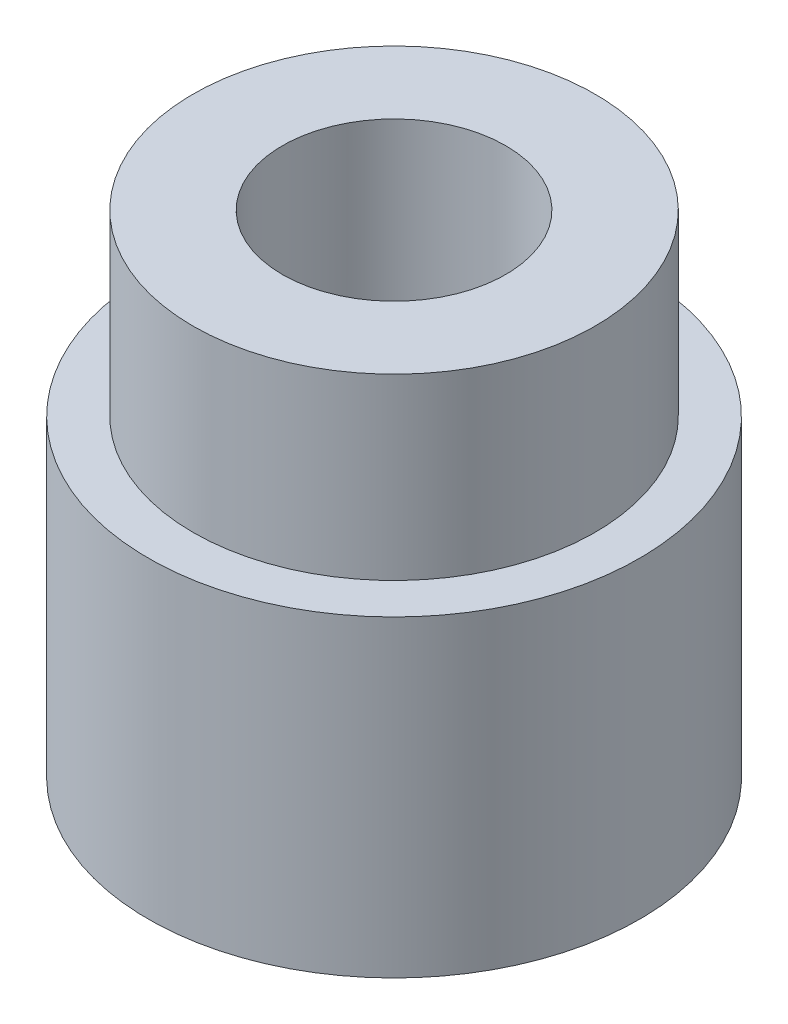
SolidWorks part; units mm, degrees
ref_plane "Front Plane" through (0, 0, 0) normal (0, 0, 1) x (1, 0, 0)
ref_plane "Top Plane" through (0, 0, 0) normal (0, 1, 0) x (1, 0, 0)
ref_plane "Right Plane" through (0, 0, 0) normal (1, 0, 0) x (0, 0, -1)
sketch "Sketch1" plane through (0, 0, 0) normal (0, 1, 0) x (1, 0, 0)
  circle A0 centre (0, 0) radius 4.5
  circle A1 centre (0, 0) radius 2.5
  dimension "D1" = 9
  dimension "D2" = 5
extrude "Boss-Extrude1" add sketch "Sketch1" along normal blind 4
sketch "Sketch2" plane through (0, 0, 0) normal (0, -1, 0) x (1, 0, 0)
  circle A0 centre (0, 0) radius 5.5
  circle A1 centre (0, 0) radius 2.5 construction
  circle A2 centre (0, 0) radius 2.5
  dimension "D1" = 11
extrude "Boss-Extrude2" add sketch "Sketch2" along normal blind 7
sketch "Sketch3" [suppressed] plane through (0, -7, 0) normal (0, -1, 0) x (1, 0, 0)
  line L0 (-0.1, 5.4991) -> (0, 5.3873)
  line L1 (0, 5.3873) -> (0.1, 5.4991)
  line L2 (0, 0) -> (0, 4.3381) construction
  line L3 (0.1033, 5.499) -> (0.1991, 5.3836)
  line L4 (0.1991, 5.3836) -> (0.3031, 5.4916)
  line L5 (0.3064, 5.4915) -> (0.3979, 5.3726)
  line L6 (0.3979, 5.3726) -> (0.5058, 5.4767)
  line L7 (0.5091, 5.4764) -> (0.5961, 5.3542)
  line L8 (0.5961, 5.3542) -> (0.7079, 5.4543)
  line L9 (0.7111, 5.4538) -> (0.7936, 5.3285)
  line L10 (0.7936, 5.3285) -> (0.9089, 5.4244)
  line L11 (0.9122, 5.4238) -> (0.9899, 5.2956)
  line L12 (0.9899, 5.2956) -> (1.1088, 5.3871)
  line L13 (1.112, 5.3864) -> (1.1849, 5.2554)
  line L14 (1.1849, 5.2554) -> (1.3071, 5.3424)
  line L15 (1.3102, 5.3417) -> (1.3783, 5.208)
  line L16 (1.3783, 5.208) -> (1.5036, 5.2905)
  line L17 (1.5067, 5.2896) -> (1.5698, 5.1535)
  line L18 (1.5698, 5.1535) -> (1.698, 5.2313)
  line L19 (1.7011, 5.2303) -> (1.7592, 5.092)
  line L20 (1.7592, 5.092) -> (1.8902, 5.165)
  line L21 (1.8933, 5.1639) -> (1.9461, 5.0235)
  line L22 (1.9461, 5.0235) -> (2.0797, 5.0916)
  line L23 (2.0828, 5.0904) -> (2.1304, 4.9482)
  line L24 (2.1304, 4.9482) -> (2.2665, 5.0113)
  line L25 (2.2694, 5.01) -> (2.3118, 4.8661)
  line L26 (2.3118, 4.8661) -> (2.4501, 4.9241)
  line L27 (2.453, 4.9227) -> (2.49, 4.7773)
  line L28 (2.49, 4.7773) -> (2.6304, 4.8302)
  line L29 (2.6332, 4.8287) -> (2.6649, 4.682)
  line L30 (2.6649, 4.682) -> (2.8071, 4.7297)
  line L31 (2.8099, 4.7281) -> (2.836, 4.5804)
  line L32 (2.836, 4.5804) -> (2.9799, 4.6228)
  line L33 (2.9827, 4.621) -> (3.0034, 4.4724)
  line L34 (3.0034, 4.4724) -> (3.1487, 4.5095)
  line L35 (3.1514, 4.5076) -> (3.1666, 4.3584)
  line L36 (3.1666, 4.3584) -> (3.3132, 4.3901)
  line L37 (3.3158, 4.3881) -> (3.3255, 4.2384)
  line L38 (3.3255, 4.2384) -> (3.4731, 4.2647)
  line L39 (3.4757, 4.2626) -> (3.4798, 4.1126)
  line L40 (3.4798, 4.1126) -> (3.6284, 4.1334)
  line L41 (3.6308, 4.1312) -> (3.6294, 3.9813)
  line L42 (3.6294, 3.9813) -> (3.7786, 3.9965)
  line L43 (3.781, 3.9943) -> (3.774, 3.8444)
  line L44 (3.774, 3.8444) -> (3.9237, 3.8542)
  line L45 (3.926, 3.8518) -> (3.9135, 3.7023)
  line L46 (3.9135, 3.7023) -> (4.0634, 3.7065)
  line L47 (4.0656, 3.7041) -> (4.0476, 3.5552)
  line L48 (4.0476, 3.5552) -> (4.1976, 3.5539)
  line L49 (4.1997, 3.5514) -> (4.1762, 3.4032)
  line L50 (4.1762, 3.4032) -> (4.3261, 3.3963)
  line L51 (4.3281, 3.3937) -> (4.2991, 3.2466)
  line L52 (4.2991, 3.2466) -> (4.4486, 3.2341)
  line L53 (4.4506, 3.2315) -> (4.4162, 3.0855)
  line L54 (4.4162, 3.0855) -> (4.5651, 3.0675)
  line L55 (4.5669, 3.0648) -> (4.5272, 2.9202)
  line L56 (4.5272, 2.9202) -> (4.6753, 2.8968)
  line L57 (4.6771, 2.894) -> (4.632, 2.7509)
  line L58 (4.632, 2.7509) -> (4.7792, 2.722)
  line L59 (4.7808, 2.7192) -> (4.7305, 2.5779)
  line L60 (4.7305, 2.5779) -> (4.8765, 2.5436)
  line L61 (4.878, 2.5407) -> (4.8225, 2.4013)
  line L62 (4.8225, 2.4013) -> (4.9672, 2.3616)
  line L63 (4.9686, 2.3587) -> (4.9079, 2.2215)
  line L64 (4.9079, 2.2215) -> (5.051, 2.1765)
  line L65 (5.0523, 2.1735) -> (4.9867, 2.0386)
  line L66 (4.9867, 2.0386) -> (5.128, 1.9884)
  line L67 (5.1292, 1.9853) -> (5.0586, 1.853)
  line L68 (5.0586, 1.853) -> (5.198, 1.7975)
  line L69 (5.199, 1.7944) -> (5.1236, 1.6648)
  line L70 (5.1236, 1.6648) -> (5.2608, 1.6042)
  line L71 (5.2618, 1.6011) -> (5.1816, 1.4743)
  line L72 (5.1816, 1.4743) -> (5.3165, 1.4087)
  line L73 (5.3174, 1.4056) -> (5.2326, 1.2818)
  line L74 (5.2326, 1.2818) -> (5.365, 1.2113)
  line L75 (5.3657, 1.2081) -> (5.2764, 1.0876)
  line L76 (5.2764, 1.0876) -> (5.4061, 1.0122)
  line L77 (5.4067, 1.009) -> (5.3129, 0.8919)
  line L78 (5.3129, 0.8919) -> (5.4398, 0.8118)
  line L79 (5.4402, 0.8085) -> (5.3423, 0.695)
  line L80 (5.3423, 0.695) -> (5.466, 0.6102)
  line L81 (5.4664, 0.607) -> (5.3643, 0.4971)
  line L82 (5.3643, 0.4971) -> (5.4849, 0.4078)
  line L83 (5.4851, 0.4046) -> (5.379, 0.2985)
  line L84 (5.379, 0.2985) -> (5.4962, 0.2049)
  line L85 (5.4963, 0.2016) -> (5.3864, 0.0996)
  line L86 (5.3864, 0.0996) -> (5.5, 0.0016)
  line L87 (5.5, -0.0016) -> (5.3864, -0.0996)
  line L88 (5.3864, -0.0996) -> (5.4963, -0.2016)
  line L89 (5.4962, -0.2049) -> (5.379, -0.2985)
  line L90 (5.379, -0.2985) -> (5.4851, -0.4046)
  line L91 (5.4849, -0.4078) -> (5.3643, -0.4971)
  line L92 (5.3643, -0.4971) -> (5.4664, -0.607)
  line L93 (5.466, -0.6102) -> (5.3423, -0.695)
  line L94 (5.3423, -0.695) -> (5.4402, -0.8085)
  line L95 (5.4398, -0.8118) -> (5.3129, -0.8919)
  line L96 (5.3129, -0.8919) -> (5.4067, -1.009)
  line L97 (5.4061, -1.0122) -> (5.2764, -1.0876)
  line L98 (5.2764, -1.0876) -> (5.3657, -1.2081)
  line L99 (5.365, -1.2113) -> (5.2326, -1.2818)
  line L100 (5.2326, -1.2818) -> (5.3174, -1.4056)
  line L101 (5.3165, -1.4087) -> (5.1816, -1.4743)
  line L102 (5.1816, -1.4743) -> (5.2618, -1.6011)
  line L103 (5.2608, -1.6042) -> (5.1236, -1.6648)
  line L104 (5.1236, -1.6648) -> (5.199, -1.7944)
  line L105 (5.198, -1.7975) -> (5.0586, -1.853)
  line L106 (5.0586, -1.853) -> (5.1292, -1.9853)
  line L107 (5.128, -1.9884) -> (4.9867, -2.0386)
  line L108 (4.9867, -2.0386) -> (5.0523, -2.1735)
  line L109 (5.051, -2.1765) -> (4.9079, -2.2215)
  line L110 (4.9079, -2.2215) -> (4.9686, -2.3587)
  line L111 (4.9672, -2.3616) -> (4.8225, -2.4013)
  line L112 (4.8225, -2.4013) -> (4.878, -2.5407)
  line L113 (4.8765, -2.5436) -> (4.7305, -2.5779)
  line L114 (4.7305, -2.5779) -> (4.7808, -2.7192)
  line L115 (4.7792, -2.722) -> (4.632, -2.7509)
  line L116 (4.632, -2.7509) -> (4.6771, -2.894)
  line L117 (4.6753, -2.8968) -> (4.5272, -2.9202)
  line L118 (4.5272, -2.9202) -> (4.5669, -3.0648)
  line L119 (4.5651, -3.0675) -> (4.4162, -3.0855)
  line L120 (4.4162, -3.0855) -> (4.4506, -3.2315)
  line L121 (4.4486, -3.2341) -> (4.2991, -3.2466)
  line L122 (4.2991, -3.2466) -> (4.3281, -3.3937)
  line L123 (4.3261, -3.3963) -> (4.1762, -3.4032)
  line L124 (4.1762, -3.4032) -> (4.1997, -3.5514)
  line L125 (4.1976, -3.5539) -> (4.0476, -3.5552)
  line L126 (4.0476, -3.5552) -> (4.0656, -3.7041)
  line L127 (4.0634, -3.7065) -> (3.9135, -3.7023)
  line L128 (3.9135, -3.7023) -> (3.926, -3.8518)
  line L129 (3.9237, -3.8542) -> (3.774, -3.8444)
  line L130 (3.774, -3.8444) -> (3.781, -3.9943)
  line L131 (3.7786, -3.9965) -> (3.6294, -3.9813)
  line L132 (3.6294, -3.9813) -> (3.6308, -4.1312)
  line L133 (3.6284, -4.1334) -> (3.4798, -4.1126)
  line L134 (3.4798, -4.1126) -> (3.4757, -4.2626)
  line L135 (3.4731, -4.2647) -> (3.3255, -4.2384)
  line L136 (3.3255, -4.2384) -> (3.3158, -4.3881)
  line L137 (3.3132, -4.3901) -> (3.1666, -4.3584)
  line L138 (3.1666, -4.3584) -> (3.1514, -4.5076)
  line L139 (3.1487, -4.5095) -> (3.0034, -4.4724)
  line L140 (3.0034, -4.4724) -> (2.9827, -4.621)
  line L141 (2.9799, -4.6228) -> (2.836, -4.5804)
  line L142 (2.836, -4.5804) -> (2.8099, -4.7281)
  line L143 (2.8071, -4.7297) -> (2.6649, -4.682)
  line L144 (2.6649, -4.682) -> (2.6332, -4.8287)
  line L145 (2.6304, -4.8302) -> (2.49, -4.7773)
  line L146 (2.49, -4.7773) -> (2.453, -4.9227)
  line L147 (2.4501, -4.9241) -> (2.3118, -4.8661)
  line L148 (2.3118, -4.8661) -> (2.2694, -5.01)
  line L149 (2.2665, -5.0113) -> (2.1304, -4.9482)
  line L150 (2.1304, -4.9482) -> (2.0828, -5.0904)
  line L151 (2.0797, -5.0916) -> (1.9461, -5.0235)
  line L152 (1.9461, -5.0235) -> (1.8933, -5.1639)
  line L153 (1.8902, -5.165) -> (1.7592, -5.092)
  line L154 (1.7592, -5.092) -> (1.7011, -5.2303)
  line L155 (1.698, -5.2313) -> (1.5698, -5.1535)
  line L156 (1.5698, -5.1535) -> (1.5067, -5.2896)
  line L157 (1.5036, -5.2905) -> (1.3783, -5.208)
  line L158 (1.3783, -5.208) -> (1.3102, -5.3417)
  line L159 (1.3071, -5.3424) -> (1.1849, -5.2554)
  line L160 (1.1849, -5.2554) -> (1.112, -5.3864)
  line L161 (1.1088, -5.3871) -> (0.9899, -5.2956)
  line L162 (0.9899, -5.2956) -> (0.9122, -5.4238)
  line L163 (0.9089, -5.4244) -> (0.7936, -5.3285)
  line L164 (0.7936, -5.3285) -> (0.7111, -5.4538)
  line L165 (0.7079, -5.4543) -> (0.5961, -5.3542)
  line L166 (0.5961, -5.3542) -> (0.5091, -5.4764)
  line L167 (0.5058, -5.4767) -> (0.3979, -5.3726)
  line L168 (0.3979, -5.3726) -> (0.3064, -5.4915)
  line L169 (0.3031, -5.4916) -> (0.1991, -5.3836)
  line L170 (0.1991, -5.3836) -> (0.1033, -5.499)
  line L171 (0.1, -5.4991) -> (0, -5.3873)
  line L172 (0, -5.3873) -> (-0.1, -5.4991)
  line L173 (-0.1033, -5.499) -> (-0.1991, -5.3836)
  line L174 (-0.1991, -5.3836) -> (-0.3031, -5.4916)
  line L175 (-0.3064, -5.4915) -> (-0.3979, -5.3726)
  line L176 (-0.3979, -5.3726) -> (-0.5058, -5.4767)
  line L177 (-0.5091, -5.4764) -> (-0.5961, -5.3542)
  line L178 (-0.5961, -5.3542) -> (-0.7079, -5.4543)
  line L179 (-0.7111, -5.4538) -> (-0.7936, -5.3285)
  line L180 (-0.7936, -5.3285) -> (-0.9089, -5.4244)
  line L181 (-0.9122, -5.4238) -> (-0.9899, -5.2956)
  line L182 (-0.9899, -5.2956) -> (-1.1088, -5.3871)
  line L183 (-1.112, -5.3864) -> (-1.1849, -5.2554)
  line L184 (-1.1849, -5.2554) -> (-1.3071, -5.3424)
  line L185 (-1.3102, -5.3417) -> (-1.3783, -5.208)
  line L186 (-1.3783, -5.208) -> (-1.5036, -5.2905)
  line L187 (-1.5067, -5.2896) -> (-1.5698, -5.1535)
  line L188 (-1.5698, -5.1535) -> (-1.698, -5.2313)
  line L189 (-1.7011, -5.2303) -> (-1.7592, -5.092)
  line L190 (-1.7592, -5.092) -> (-1.8902, -5.165)
  line L191 (-1.8933, -5.1639) -> (-1.9461, -5.0235)
  line L192 (-1.9461, -5.0235) -> (-2.0797, -5.0916)
  line L193 (-2.0828, -5.0904) -> (-2.1304, -4.9482)
  line L194 (-2.1304, -4.9482) -> (-2.2665, -5.0113)
  line L195 (-2.2694, -5.01) -> (-2.3118, -4.8661)
  line L196 (-2.3118, -4.8661) -> (-2.4501, -4.9241)
  line L197 (-2.453, -4.9227) -> (-2.49, -4.7773)
  line L198 (-2.49, -4.7773) -> (-2.6304, -4.8302)
  line L199 (-2.6332, -4.8287) -> (-2.6649, -4.682)
  line L200 (-2.6649, -4.682) -> (-2.8071, -4.7297)
  line L201 (-2.8099, -4.7281) -> (-2.836, -4.5804)
  line L202 (-2.836, -4.5804) -> (-2.9799, -4.6228)
  line L203 (-2.9827, -4.621) -> (-3.0034, -4.4724)
  line L204 (-3.0034, -4.4724) -> (-3.1487, -4.5095)
  line L205 (-3.1514, -4.5076) -> (-3.1666, -4.3584)
  line L206 (-3.1666, -4.3584) -> (-3.3132, -4.3901)
  line L207 (-3.3158, -4.3881) -> (-3.3255, -4.2384)
  line L208 (-3.3255, -4.2384) -> (-3.4731, -4.2647)
  line L209 (-3.4757, -4.2626) -> (-3.4798, -4.1126)
  line L210 (-3.4798, -4.1126) -> (-3.6284, -4.1334)
  line L211 (-3.6308, -4.1312) -> (-3.6294, -3.9813)
  line L212 (-3.6294, -3.9813) -> (-3.7786, -3.9965)
  line L213 (-3.781, -3.9943) -> (-3.774, -3.8444)
  line L214 (-3.774, -3.8444) -> (-3.9237, -3.8542)
  line L215 (-3.926, -3.8518) -> (-3.9135, -3.7023)
  line L216 (-3.9135, -3.7023) -> (-4.0634, -3.7065)
  line L217 (-4.0656, -3.7041) -> (-4.0476, -3.5552)
  line L218 (-4.0476, -3.5552) -> (-4.1976, -3.5539)
  line L219 (-4.1997, -3.5514) -> (-4.1762, -3.4032)
  line L220 (-4.1762, -3.4032) -> (-4.3261, -3.3963)
  line L221 (-4.3281, -3.3937) -> (-4.2991, -3.2466)
  line L222 (-4.2991, -3.2466) -> (-4.4486, -3.2341)
  line L223 (-4.4506, -3.2315) -> (-4.4162, -3.0855)
  line L224 (-4.4162, -3.0855) -> (-4.5651, -3.0675)
  line L225 (-4.5669, -3.0648) -> (-4.5272, -2.9202)
  line L226 (-4.5272, -2.9202) -> (-4.6753, -2.8968)
  line L227 (-4.6771, -2.894) -> (-4.632, -2.7509)
  line L228 (-4.632, -2.7509) -> (-4.7792, -2.722)
  line L229 (-4.7808, -2.7192) -> (-4.7305, -2.5779)
  line L230 (-4.7305, -2.5779) -> (-4.8765, -2.5436)
  line L231 (-4.878, -2.5407) -> (-4.8225, -2.4013)
  line L232 (-4.8225, -2.4013) -> (-4.9672, -2.3616)
  line L233 (-4.9686, -2.3587) -> (-4.9079, -2.2215)
  line L234 (-4.9079, -2.2215) -> (-5.051, -2.1765)
  line L235 (-5.0523, -2.1735) -> (-4.9867, -2.0386)
  line L236 (-4.9867, -2.0386) -> (-5.128, -1.9884)
  line L237 (-5.1292, -1.9853) -> (-5.0586, -1.853)
  line L238 (-5.0586, -1.853) -> (-5.198, -1.7975)
  line L239 (-5.199, -1.7944) -> (-5.1236, -1.6648)
  line L240 (-5.1236, -1.6648) -> (-5.2608, -1.6042)
  line L241 (-5.2618, -1.6011) -> (-5.1816, -1.4743)
  line L242 (-5.1816, -1.4743) -> (-5.3165, -1.4087)
  line L243 (-5.3174, -1.4056) -> (-5.2326, -1.2818)
  line L244 (-5.2326, -1.2818) -> (-5.365, -1.2113)
  line L245 (-5.3657, -1.2081) -> (-5.2764, -1.0876)
  line L246 (-5.2764, -1.0876) -> (-5.4061, -1.0122)
  line L247 (-5.4067, -1.009) -> (-5.3129, -0.8919)
  line L248 (-5.3129, -0.8919) -> (-5.4398, -0.8118)
  line L249 (-5.4402, -0.8085) -> (-5.3423, -0.695)
  line L250 (-5.3423, -0.695) -> (-5.466, -0.6102)
  line L251 (-5.4664, -0.607) -> (-5.3643, -0.4971)
  line L252 (-5.3643, -0.4971) -> (-5.4849, -0.4078)
  line L253 (-5.4851, -0.4046) -> (-5.379, -0.2985)
  line L254 (-5.379, -0.2985) -> (-5.4962, -0.2049)
  line L255 (-5.4963, -0.2016) -> (-5.3864, -0.0996)
  line L256 (-5.3864, -0.0996) -> (-5.5, -0.0016)
  line L257 (-5.5, 0.0016) -> (-5.3864, 0.0996)
  line L258 (-5.3864, 0.0996) -> (-5.4963, 0.2016)
  line L259 (-5.4962, 0.2049) -> (-5.379, 0.2985)
  line L260 (-5.379, 0.2985) -> (-5.4851, 0.4046)
  line L261 (-5.4849, 0.4078) -> (-5.3643, 0.4971)
  line L262 (-5.3643, 0.4971) -> (-5.4664, 0.607)
  line L263 (-5.466, 0.6102) -> (-5.3423, 0.695)
  line L264 (-5.3423, 0.695) -> (-5.4402, 0.8085)
  line L265 (-5.4398, 0.8118) -> (-5.3129, 0.8919)
  line L266 (-5.3129, 0.8919) -> (-5.4067, 1.009)
  line L267 (-5.4061, 1.0122) -> (-5.2764, 1.0876)
  line L268 (-5.2764, 1.0876) -> (-5.3657, 1.2081)
  line L269 (-5.365, 1.2113) -> (-5.2326, 1.2818)
  line L270 (-5.2326, 1.2818) -> (-5.3174, 1.4056)
  line L271 (-5.3165, 1.4087) -> (-5.1816, 1.4743)
  line L272 (-5.1816, 1.4743) -> (-5.2618, 1.6011)
  line L273 (-5.2608, 1.6042) -> (-5.1236, 1.6648)
  line L274 (-5.1236, 1.6648) -> (-5.199, 1.7944)
  line L275 (-5.198, 1.7975) -> (-5.0586, 1.853)
  line L276 (-5.0586, 1.853) -> (-5.1292, 1.9853)
  line L277 (-5.128, 1.9884) -> (-4.9867, 2.0386)
  line L278 (-4.9867, 2.0386) -> (-5.0523, 2.1735)
  line L279 (-5.051, 2.1765) -> (-4.9079, 2.2215)
  line L280 (-4.9079, 2.2215) -> (-4.9686, 2.3587)
  line L281 (-4.9672, 2.3616) -> (-4.8225, 2.4013)
  line L282 (-4.8225, 2.4013) -> (-4.878, 2.5407)
  line L283 (-4.8765, 2.5436) -> (-4.7305, 2.5779)
  line L284 (-4.7305, 2.5779) -> (-4.7808, 2.7192)
  line L285 (-4.7792, 2.722) -> (-4.632, 2.7509)
  line L286 (-4.632, 2.7509) -> (-4.6771, 2.894)
  line L287 (-4.6753, 2.8968) -> (-4.5272, 2.9202)
  line L288 (-4.5272, 2.9202) -> (-4.5669, 3.0648)
  line L289 (-4.5651, 3.0675) -> (-4.4162, 3.0855)
  line L290 (-4.4162, 3.0855) -> (-4.4506, 3.2315)
  line L291 (-4.4486, 3.2341) -> (-4.2991, 3.2466)
  line L292 (-4.2991, 3.2466) -> (-4.3281, 3.3937)
  line L293 (-4.3261, 3.3963) -> (-4.1762, 3.4032)
  line L294 (-4.1762, 3.4032) -> (-4.1997, 3.5514)
  line L295 (-4.1976, 3.5539) -> (-4.0476, 3.5552)
  line L296 (-4.0476, 3.5552) -> (-4.0656, 3.7041)
  line L297 (-4.0634, 3.7065) -> (-3.9135, 3.7023)
  line L298 (-3.9135, 3.7023) -> (-3.926, 3.8518)
  line L299 (-3.9237, 3.8542) -> (-3.774, 3.8444)
  line L300 (-3.774, 3.8444) -> (-3.781, 3.9943)
  line L301 (-3.7786, 3.9965) -> (-3.6294, 3.9813)
  line L302 (-3.6294, 3.9813) -> (-3.6308, 4.1312)
  line L303 (-3.6284, 4.1334) -> (-3.4798, 4.1126)
  line L304 (-3.4798, 4.1126) -> (-3.4757, 4.2626)
  line L305 (-3.4731, 4.2647) -> (-3.3255, 4.2384)
  line L306 (-3.3255, 4.2384) -> (-3.3158, 4.3881)
  line L307 (-3.3132, 4.3901) -> (-3.1666, 4.3584)
  line L308 (-3.1666, 4.3584) -> (-3.1514, 4.5076)
  line L309 (-3.1487, 4.5095) -> (-3.0034, 4.4724)
  line L310 (-3.0034, 4.4724) -> (-2.9827, 4.621)
  line L311 (-2.9799, 4.6228) -> (-2.836, 4.5804)
  line L312 (-2.836, 4.5804) -> (-2.8099, 4.7281)
  line L313 (-2.8071, 4.7297) -> (-2.6649, 4.682)
  line L314 (-2.6649, 4.682) -> (-2.6332, 4.8287)
  line L315 (-2.6304, 4.8302) -> (-2.49, 4.7773)
  line L316 (-2.49, 4.7773) -> (-2.453, 4.9227)
  line L317 (-2.4501, 4.9241) -> (-2.3118, 4.8661)
  line L318 (-2.3118, 4.8661) -> (-2.2694, 5.01)
  line L319 (-2.2665, 5.0113) -> (-2.1304, 4.9482)
  line L320 (-2.1304, 4.9482) -> (-2.0828, 5.0904)
  line L321 (-2.0797, 5.0916) -> (-1.9461, 5.0235)
  line L322 (-1.9461, 5.0235) -> (-1.8933, 5.1639)
  line L323 (-1.8902, 5.165) -> (-1.7592, 5.092)
  line L324 (-1.7592, 5.092) -> (-1.7011, 5.2303)
  line L325 (-1.698, 5.2313) -> (-1.5698, 5.1535)
  line L326 (-1.5698, 5.1535) -> (-1.5067, 5.2896)
  line L327 (-1.5036, 5.2905) -> (-1.3783, 5.208)
  line L328 (-1.3783, 5.208) -> (-1.3102, 5.3417)
  line L329 (-1.3071, 5.3424) -> (-1.1849, 5.2554)
  line L330 (-1.1849, 5.2554) -> (-1.112, 5.3864)
  line L331 (-1.1088, 5.3871) -> (-0.9899, 5.2956)
  line L332 (-0.9899, 5.2956) -> (-0.9122, 5.4238)
  line L333 (-0.9089, 5.4244) -> (-0.7936, 5.3285)
  line L334 (-0.7936, 5.3285) -> (-0.7111, 5.4538)
  line L335 (-0.7079, 5.4543) -> (-0.5961, 5.3542)
  line L336 (-0.5961, 5.3542) -> (-0.5091, 5.4764)
  line L337 (-0.5058, 5.4767) -> (-0.3979, 5.3726)
  line L338 (-0.3979, 5.3726) -> (-0.3064, 5.4915)
  line L339 (-0.3031, 5.4916) -> (-0.1991, 5.3836)
  line L340 (-0.1991, 5.3836) -> (-0.1033, 5.499)
  circle A1 centre (0, 0) radius 5.5 construction
  arc A2 (0.1, 5.4991) -> (-0.1, 5.4991) centre (0, 0) ccw
  arc A3 (0.3031, 5.4916) -> (0.1033, 5.499) centre (0, 0) ccw
  arc A4 (0.5058, 5.4767) -> (0.3064, 5.4915) centre (0, 0) ccw
  arc A5 (0.7079, 5.4543) -> (0.5091, 5.4764) centre (0, 0) ccw
  arc A6 (0.9089, 5.4244) -> (0.7111, 5.4538) centre (0, 0) ccw
  arc A7 (1.1088, 5.3871) -> (0.9122, 5.4238) centre (0, 0) ccw
  arc A8 (1.3071, 5.3424) -> (1.112, 5.3864) centre (0, 0) ccw
  arc A9 (1.5036, 5.2905) -> (1.3102, 5.3417) centre (0, 0) ccw
  arc A10 (1.698, 5.2313) -> (1.5067, 5.2896) centre (0, 0) ccw
  arc A11 (1.8902, 5.165) -> (1.7011, 5.2303) centre (0, 0) ccw
  arc A12 (2.0797, 5.0916) -> (1.8933, 5.1639) centre (0, 0) ccw
  arc A13 (2.2665, 5.0113) -> (2.0828, 5.0904) centre (0, 0) ccw
  arc A14 (2.4501, 4.9241) -> (2.2694, 5.01) centre (0, 0) ccw
  arc A15 (2.6304, 4.8302) -> (2.453, 4.9227) centre (0, 0) ccw
  arc A16 (2.8071, 4.7297) -> (2.6332, 4.8287) centre (0, 0) ccw
  arc A17 (2.9799, 4.6228) -> (2.8099, 4.7281) centre (0, 0) ccw
  arc A18 (3.1487, 4.5095) -> (2.9827, 4.621) centre (0, 0) ccw
  arc A19 (3.3132, 4.3901) -> (3.1514, 4.5076) centre (0, 0) ccw
  arc A20 (3.4731, 4.2647) -> (3.3158, 4.3881) centre (0, 0) ccw
  arc A21 (3.6284, 4.1334) -> (3.4757, 4.2626) centre (0, 0) ccw
  arc A22 (3.7786, 3.9965) -> (3.6308, 4.1312) centre (0, 0) ccw
  arc A23 (3.9237, 3.8542) -> (3.781, 3.9943) centre (0, 0) ccw
  arc A24 (4.0634, 3.7065) -> (3.926, 3.8518) centre (0, 0) ccw
  arc A25 (4.1976, 3.5539) -> (4.0656, 3.7041) centre (0, 0) ccw
  arc A26 (4.3261, 3.3963) -> (4.1997, 3.5514) centre (0, 0) ccw
  arc A27 (4.4486, 3.2341) -> (4.3281, 3.3937) centre (0, 0) ccw
  arc A28 (4.5651, 3.0675) -> (4.4506, 3.2315) centre (0, 0) ccw
  arc A29 (4.6753, 2.8968) -> (4.5669, 3.0648) centre (0, 0) ccw
  arc A30 (4.7792, 2.722) -> (4.6771, 2.894) centre (0, 0) ccw
  arc A31 (4.8765, 2.5436) -> (4.7808, 2.7192) centre (0, 0) ccw
  arc A32 (4.9672, 2.3616) -> (4.878, 2.5407) centre (0, 0) ccw
  arc A33 (5.051, 2.1765) -> (4.9686, 2.3587) centre (0, 0) ccw
  arc A34 (5.128, 1.9884) -> (5.0523, 2.1735) centre (0, 0) ccw
  arc A35 (5.198, 1.7975) -> (5.1292, 1.9853) centre (0, 0) ccw
  arc A36 (5.2608, 1.6042) -> (5.199, 1.7944) centre (0, 0) ccw
  arc A37 (5.3165, 1.4087) -> (5.2618, 1.6011) centre (0, 0) ccw
  arc A38 (5.365, 1.2113) -> (5.3174, 1.4056) centre (0, 0) ccw
  arc A39 (5.4061, 1.0122) -> (5.3657, 1.2081) centre (0, 0) ccw
  arc A40 (5.4398, 0.8118) -> (5.4067, 1.009) centre (0, 0) ccw
  arc A41 (5.466, 0.6102) -> (5.4402, 0.8085) centre (0, 0) ccw
  arc A42 (5.4849, 0.4078) -> (5.4664, 0.607) centre (0, 0) ccw
  arc A43 (5.4962, 0.2049) -> (5.4851, 0.4046) centre (0, 0) ccw
  arc A44 (5.5, 0.0016) -> (5.4963, 0.2016) centre (0, 0) ccw
  arc A45 (5.4963, -0.2016) -> (5.5, -0.0016) centre (0, 0) ccw
  arc A46 (5.4851, -0.4046) -> (5.4962, -0.2049) centre (0, 0) ccw
  arc A47 (5.4664, -0.607) -> (5.4849, -0.4078) centre (0, 0) ccw
  arc A48 (5.4402, -0.8085) -> (5.466, -0.6102) centre (0, 0) ccw
  arc A49 (5.4067, -1.009) -> (5.4398, -0.8118) centre (0, 0) ccw
  arc A50 (5.3657, -1.2081) -> (5.4061, -1.0122) centre (0, 0) ccw
  arc A51 (5.3174, -1.4056) -> (5.365, -1.2113) centre (0, 0) ccw
  arc A52 (5.2618, -1.6011) -> (5.3165, -1.4087) centre (0, 0) ccw
  arc A53 (5.199, -1.7944) -> (5.2608, -1.6042) centre (0, 0) ccw
  arc A54 (5.1292, -1.9853) -> (5.198, -1.7975) centre (0, 0) ccw
  arc A55 (5.0523, -2.1735) -> (5.128, -1.9884) centre (0, 0) ccw
  arc A56 (4.9686, -2.3587) -> (5.051, -2.1765) centre (0, 0) ccw
  arc A57 (4.878, -2.5407) -> (4.9672, -2.3616) centre (0, 0) ccw
  arc A58 (4.7808, -2.7192) -> (4.8765, -2.5436) centre (0, 0) ccw
  arc A59 (4.6771, -2.894) -> (4.7792, -2.722) centre (0, 0) ccw
  arc A60 (4.5669, -3.0648) -> (4.6753, -2.8968) centre (0, 0) ccw
  arc A61 (4.4506, -3.2315) -> (4.5651, -3.0675) centre (0, 0) ccw
  arc A62 (4.3281, -3.3937) -> (4.4486, -3.2341) centre (0, 0) ccw
  arc A63 (4.1997, -3.5514) -> (4.3261, -3.3963) centre (0, 0) ccw
  arc A64 (4.0656, -3.7041) -> (4.1976, -3.5539) centre (0, 0) ccw
  arc A65 (3.926, -3.8518) -> (4.0634, -3.7065) centre (0, 0) ccw
  arc A66 (3.781, -3.9943) -> (3.9237, -3.8542) centre (0, 0) ccw
  arc A67 (3.6308, -4.1312) -> (3.7786, -3.9965) centre (0, 0) ccw
  arc A68 (3.4757, -4.2626) -> (3.6284, -4.1334) centre (0, 0) ccw
  arc A69 (3.3158, -4.3881) -> (3.4731, -4.2647) centre (0, 0) ccw
  arc A70 (3.1514, -4.5076) -> (3.3132, -4.3901) centre (0, 0) ccw
  arc A71 (2.9827, -4.621) -> (3.1487, -4.5095) centre (0, 0) ccw
  arc A72 (2.8099, -4.7281) -> (2.9799, -4.6228) centre (0, 0) ccw
  arc A73 (2.6332, -4.8287) -> (2.8071, -4.7297) centre (0, 0) ccw
  arc A74 (2.453, -4.9227) -> (2.6304, -4.8302) centre (0, 0) ccw
  arc A75 (2.2694, -5.01) -> (2.4501, -4.9241) centre (0, 0) ccw
  arc A76 (2.0828, -5.0904) -> (2.2665, -5.0113) centre (0, 0) ccw
  arc A77 (1.8933, -5.1639) -> (2.0797, -5.0916) centre (0, 0) ccw
  arc A78 (1.7011, -5.2303) -> (1.8902, -5.165) centre (0, 0) ccw
  arc A79 (1.5067, -5.2896) -> (1.698, -5.2313) centre (0, 0) ccw
  arc A80 (1.3102, -5.3417) -> (1.5036, -5.2905) centre (0, 0) ccw
  arc A81 (1.112, -5.3864) -> (1.3071, -5.3424) centre (0, 0) ccw
  arc A82 (0.9122, -5.4238) -> (1.1088, -5.3871) centre (0, 0) ccw
  arc A83 (0.7111, -5.4538) -> (0.9089, -5.4244) centre (0, 0) ccw
  arc A84 (0.5091, -5.4764) -> (0.7079, -5.4543) centre (0, 0) ccw
  arc A85 (0.3064, -5.4915) -> (0.5058, -5.4767) centre (0, 0) ccw
  arc A86 (0.1033, -5.499) -> (0.3031, -5.4916) centre (0, 0) ccw
  arc A87 (-0.1, -5.4991) -> (0.1, -5.4991) centre (0, 0) ccw
  arc A88 (-0.3031, -5.4916) -> (-0.1033, -5.499) centre (0, 0) ccw
  arc A89 (-0.5058, -5.4767) -> (-0.3064, -5.4915) centre (0, 0) ccw
  arc A90 (-0.7079, -5.4543) -> (-0.5091, -5.4764) centre (0, 0) ccw
  arc A91 (-0.9089, -5.4244) -> (-0.7111, -5.4538) centre (0, 0) ccw
  arc A92 (-1.1088, -5.3871) -> (-0.9122, -5.4238) centre (0, 0) ccw
  arc A93 (-1.3071, -5.3424) -> (-1.112, -5.3864) centre (0, 0) ccw
  arc A94 (-1.5036, -5.2905) -> (-1.3102, -5.3417) centre (0, 0) ccw
  arc A95 (-1.698, -5.2313) -> (-1.5067, -5.2896) centre (0, 0) ccw
  arc A96 (-1.8902, -5.165) -> (-1.7011, -5.2303) centre (0, 0) ccw
  arc A97 (-2.0797, -5.0916) -> (-1.8933, -5.1639) centre (0, 0) ccw
  arc A98 (-2.2665, -5.0113) -> (-2.0828, -5.0904) centre (0, 0) ccw
  arc A99 (-2.4501, -4.9241) -> (-2.2694, -5.01) centre (0, 0) ccw
  arc A100 (-2.6304, -4.8302) -> (-2.453, -4.9227) centre (0, 0) ccw
  arc A101 (-2.8071, -4.7297) -> (-2.6332, -4.8287) centre (0, 0) ccw
  arc A102 (-2.9799, -4.6228) -> (-2.8099, -4.7281) centre (0, 0) ccw
  arc A103 (-3.1487, -4.5095) -> (-2.9827, -4.621) centre (0, 0) ccw
  arc A104 (-3.3132, -4.3901) -> (-3.1514, -4.5076) centre (0, 0) ccw
  arc A105 (-3.4731, -4.2647) -> (-3.3158, -4.3881) centre (0, 0) ccw
  arc A106 (-3.6284, -4.1334) -> (-3.4757, -4.2626) centre (0, 0) ccw
  arc A107 (-3.7786, -3.9965) -> (-3.6308, -4.1312) centre (0, 0) ccw
  arc A108 (-3.9237, -3.8542) -> (-3.781, -3.9943) centre (0, 0) ccw
  arc A109 (-4.0634, -3.7065) -> (-3.926, -3.8518) centre (0, 0) ccw
  arc A110 (-4.1976, -3.5539) -> (-4.0656, -3.7041) centre (0, 0) ccw
  arc A111 (-4.3261, -3.3963) -> (-4.1997, -3.5514) centre (0, 0) ccw
  arc A112 (-4.4486, -3.2341) -> (-4.3281, -3.3937) centre (0, 0) ccw
  arc A113 (-4.5651, -3.0675) -> (-4.4506, -3.2315) centre (0, 0) ccw
  arc A114 (-4.6753, -2.8968) -> (-4.5669, -3.0648) centre (0, 0) ccw
  arc A115 (-4.7792, -2.722) -> (-4.6771, -2.894) centre (0, 0) ccw
  arc A116 (-4.8765, -2.5436) -> (-4.7808, -2.7192) centre (0, 0) ccw
  arc A117 (-4.9672, -2.3616) -> (-4.878, -2.5407) centre (0, 0) ccw
  arc A118 (-5.051, -2.1765) -> (-4.9686, -2.3587) centre (0, 0) ccw
  arc A119 (-5.128, -1.9884) -> (-5.0523, -2.1735) centre (0, 0) ccw
  arc A120 (-5.198, -1.7975) -> (-5.1292, -1.9853) centre (0, 0) ccw
  arc A121 (-5.2608, -1.6042) -> (-5.199, -1.7944) centre (0, 0) ccw
  arc A122 (-5.3165, -1.4087) -> (-5.2618, -1.6011) centre (0, 0) ccw
  arc A123 (-5.365, -1.2113) -> (-5.3174, -1.4056) centre (0, 0) ccw
  arc A124 (-5.4061, -1.0122) -> (-5.3657, -1.2081) centre (0, 0) ccw
  arc A125 (-5.4398, -0.8118) -> (-5.4067, -1.009) centre (0, 0) ccw
  arc A126 (-5.466, -0.6102) -> (-5.4402, -0.8085) centre (0, 0) ccw
  arc A127 (-5.4849, -0.4078) -> (-5.4664, -0.607) centre (0, 0) ccw
  arc A128 (-5.4962, -0.2049) -> (-5.4851, -0.4046) centre (0, 0) ccw
  arc A129 (-5.5, -0.0016) -> (-5.4963, -0.2016) centre (0, 0) ccw
  arc A130 (-5.4963, 0.2016) -> (-5.5, 0.0016) centre (0, 0) ccw
  arc A131 (-5.4851, 0.4046) -> (-5.4962, 0.2049) centre (0, 0) ccw
  arc A132 (-5.4664, 0.607) -> (-5.4849, 0.4078) centre (0, 0) ccw
  arc A133 (-5.4402, 0.8085) -> (-5.466, 0.6102) centre (0, 0) ccw
  arc A134 (-5.4067, 1.009) -> (-5.4398, 0.8118) centre (0, 0) ccw
  arc A135 (-5.3657, 1.2081) -> (-5.4061, 1.0122) centre (0, 0) ccw
  arc A136 (-5.3174, 1.4056) -> (-5.365, 1.2113) centre (0, 0) ccw
  arc A137 (-5.2618, 1.6011) -> (-5.3165, 1.4087) centre (0, 0) ccw
  arc A138 (-5.199, 1.7944) -> (-5.2608, 1.6042) centre (0, 0) ccw
  arc A139 (-5.1292, 1.9853) -> (-5.198, 1.7975) centre (0, 0) ccw
  arc A140 (-5.0523, 2.1735) -> (-5.128, 1.9884) centre (0, 0) ccw
  arc A141 (-4.9686, 2.3587) -> (-5.051, 2.1765) centre (0, 0) ccw
  arc A142 (-4.878, 2.5407) -> (-4.9672, 2.3616) centre (0, 0) ccw
  arc A143 (-4.7808, 2.7192) -> (-4.8765, 2.5436) centre (0, 0) ccw
  arc A144 (-4.6771, 2.894) -> (-4.7792, 2.722) centre (0, 0) ccw
  arc A145 (-4.5669, 3.0648) -> (-4.6753, 2.8968) centre (0, 0) ccw
  arc A146 (-4.4506, 3.2315) -> (-4.5651, 3.0675) centre (0, 0) ccw
  arc A147 (-4.3281, 3.3937) -> (-4.4486, 3.2341) centre (0, 0) ccw
  arc A148 (-4.1997, 3.5514) -> (-4.3261, 3.3963) centre (0, 0) ccw
  arc A149 (-4.0656, 3.7041) -> (-4.1976, 3.5539) centre (0, 0) ccw
  arc A150 (-3.926, 3.8518) -> (-4.0634, 3.7065) centre (0, 0) ccw
  arc A151 (-3.781, 3.9943) -> (-3.9237, 3.8542) centre (0, 0) ccw
  arc A152 (-3.6308, 4.1312) -> (-3.7786, 3.9965) centre (0, 0) ccw
  arc A153 (-3.4757, 4.2626) -> (-3.6284, 4.1334) centre (0, 0) ccw
  arc A154 (-3.3158, 4.3881) -> (-3.4731, 4.2647) centre (0, 0) ccw
  arc A155 (-3.1514, 4.5076) -> (-3.3132, 4.3901) centre (0, 0) ccw
  arc A156 (-2.9827, 4.621) -> (-3.1487, 4.5095) centre (0, 0) ccw
  arc A157 (-2.8099, 4.7281) -> (-2.9799, 4.6228) centre (0, 0) ccw
  arc A158 (-2.6332, 4.8287) -> (-2.8071, 4.7297) centre (0, 0) ccw
  arc A159 (-2.453, 4.9227) -> (-2.6304, 4.8302) centre (0, 0) ccw
  arc A160 (-2.2694, 5.01) -> (-2.4501, 4.9241) centre (0, 0) ccw
  arc A161 (-2.0828, 5.0904) -> (-2.2665, 5.0113) centre (0, 0) ccw
  arc A162 (-1.8933, 5.1639) -> (-2.0797, 5.0916) centre (0, 0) ccw
  arc A163 (-1.7011, 5.2303) -> (-1.8902, 5.165) centre (0, 0) ccw
  arc A164 (-1.5067, 5.2896) -> (-1.698, 5.2313) centre (0, 0) ccw
  arc A165 (-1.3102, 5.3417) -> (-1.5036, 5.2905) centre (0, 0) ccw
  arc A166 (-1.112, 5.3864) -> (-1.3071, 5.3424) centre (0, 0) ccw
  arc A167 (-0.9122, 5.4238) -> (-1.1088, 5.3871) centre (0, 0) ccw
  arc A168 (-0.7111, 5.4538) -> (-0.9089, 5.4244) centre (0, 0) ccw
  arc A169 (-0.5091, 5.4764) -> (-0.7079, 5.4543) centre (0, 0) ccw
  arc A170 (-0.3064, 5.4915) -> (-0.5058, 5.4767) centre (0, 0) ccw
  arc A171 (-0.1033, 5.499) -> (-0.3031, 5.4916) centre (0, 0) ccw
  point P11 (0, 5.5)
  point P518 (0, 0)
  dimension "D1" = 0.2
  dimension "D2" = 0.15
  dimension "D3" = 170
